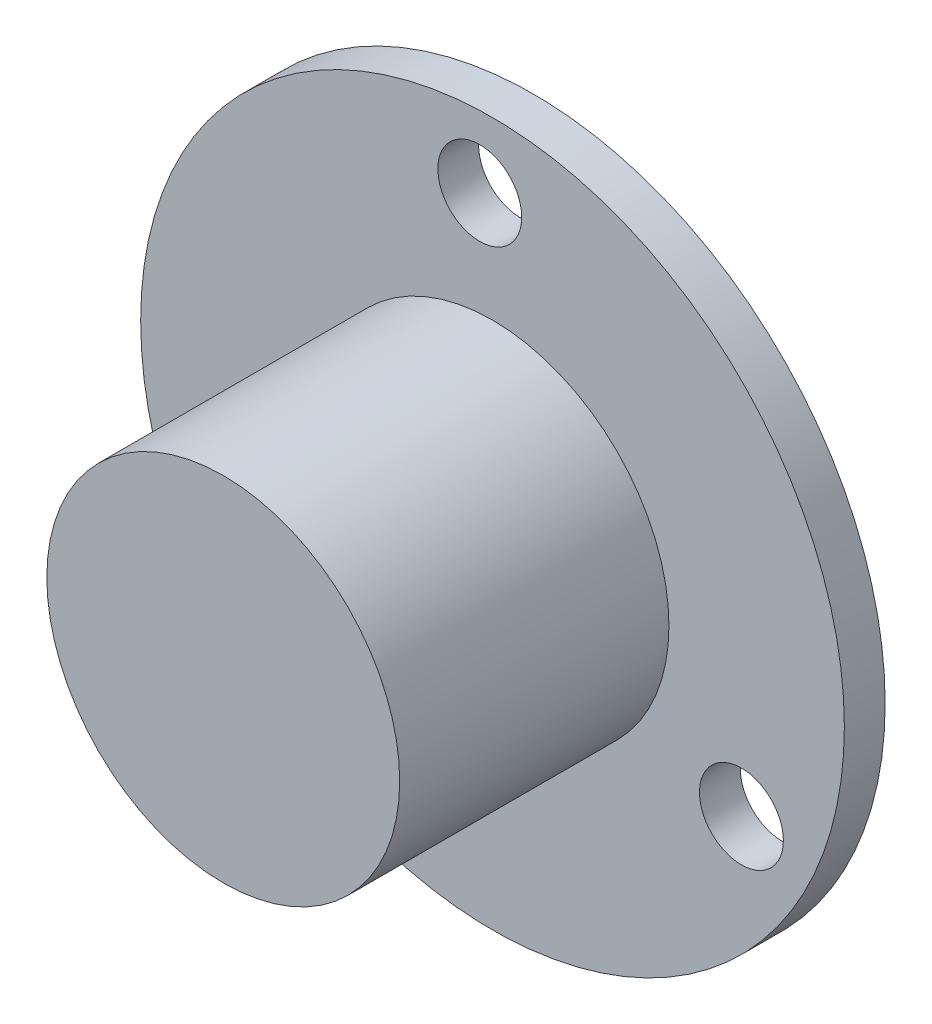
SolidWorks part; units mm, degrees
ref_plane "Front Plane" through (0, 0, 0) normal (0, 0, 1) x (1, 0, 0)
ref_plane "Top Plane" through (0, 0, 0) normal (0, 1, 0) x (1, 0, 0)
ref_plane "Right Plane" through (0, 0, 0) normal (1, 0, 0) x (0, 0, -1)
sketch "Sketch1" plane through (0, 0, 0) normal (0, 0, 1) x (1, 0, 0)
  line L0 (0, 0) -> (-0.7938, 17.4371) construction
  line L1 (0, 0) -> (-14.7041, -9.406) construction
  line L2 (0, 0) -> (15.4979, -8.0311) construction
  circle A0 centre (0, 0) radius 21.9075
  circle A1 centre (-0.7938, 17.4371) radius 2.6107
  circle A2 centre (15.4979, -8.0311) radius 2.6107
  circle A3 centre (-14.7041, -9.406) radius 2.6107
  dimension "D1" = 43.815
  dimension "D3" = 5.2213
  dimension "D2" = 17.4371
  dimension "D4" = 120
  dimension "D5" = 120
extrude "Boss-Extrude1" add sketch "Sketch1" along normal blind 2.54
sketch "Sketch2" plane through (0, 0, 0) normal (0, 0, -1) x (-1, 0, 0)
  circle A0 centre (0, 0) radius 3.8735
  dimension "D1" = 7.747
extrude "Boss-Extrude2" add sketch "Sketch2" along normal blind 8.89
sketch "Sketch3" plane through (0, 0, 2.54) normal (0, 0, 1) x (1, 0, 0)
  circle A1 centre (0, 0) radius 10.9855
  dimension "D1" = 21.971
extrude "Boss-Extrude4" add sketch "Sketch3" along normal blind 16.764
